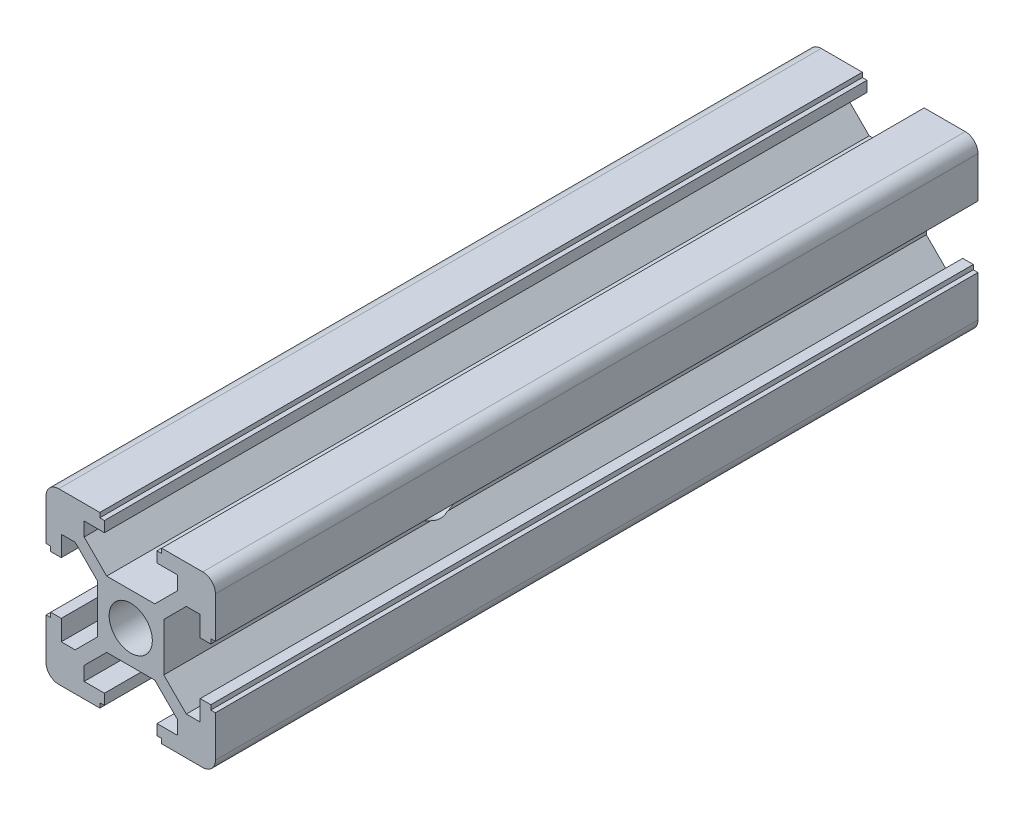
SolidWorks part; units mm, degrees
material "6063-T5"
ref_plane "前视基准面" through (0, 0, 0) normal (0, 0, 1) x (1, 0, 0)
ref_plane "上视基准面" through (0, 0, 0) normal (0, 1, 0) x (1, 0, 0)
ref_plane "右视基准面" through (0, 0, 0) normal (1, 0, 0) x (0, 0, -1)
sketch "草图2" plane through (0, 0, 0) normal (0, 0, 1) x (1, 0, 0)
  line L0 (-3.9, 2.8393) -> (-6.5607, 5.5)
  line L1 (-2.8393, 3.9) -> (2.8393, 3.9)
  line L2 (-3.9, 2.8393) -> (-3.9, -2.8393)
  line L3 (-2.8393, -3.9) -> (2.8393, -3.9)
  line L4 (3.9, 2.8393) -> (3.9, -2.8393)
  line L5 (-3.9, 3.9) -> (3.9, -3.9) construction
  line L6 (-3.9, -3.9) -> (3.9, 3.9) construction
  line L7 (-2.8393, 3.9) -> (-5.5, 6.5607)
  line L8 (-5.5, 6.5607) -> (-5.5, 8.2)
  line L9 (-5.5, 8.2) -> (-3.1, 8.2)
  line L10 (-3.1, 8.2) -> (-3.1, 9.45)
  line L11 (-3.1, 9.45) -> (-3.65, 9.45)
  line L12 (-3.65, 9.45) -> (-3.65, 10)
  line L13 (-3.65, 10) -> (-8.5, 10)
  line L14 (-6.5607, 5.5) -> (-8.2, 5.5)
  line L15 (-10, 3.65) -> (-10, 8.5)
  line L16 (-9.45, 3.65) -> (-10, 3.65)
  line L17 (-9.45, 3.1) -> (-9.45, 3.65)
  line L18 (-8.2, 3.1) -> (-9.45, 3.1)
  line L19 (-8.2, 5.5) -> (-8.2, 3.1)
  line L20 (2.8393, 3.9) -> (5.5, 6.5607)
  line L21 (3.9, 2.8393) -> (6.5607, 5.5)
  line L22 (6.5607, 5.5) -> (8.2, 5.5)
  line L23 (8.2, 5.5) -> (8.2, 3.1)
  line L24 (8.2, 3.1) -> (9.45, 3.1)
  line L25 (9.45, 3.1) -> (9.45, 3.65)
  line L26 (9.45, 3.65) -> (10, 3.65)
  line L27 (10, 3.65) -> (10, 8.5)
  line L28 (5.5, 6.5607) -> (5.5, 8.2)
  line L29 (3.65, 10) -> (8.5, 10)
  line L30 (3.65, 9.45) -> (3.65, 10)
  line L31 (3.1, 9.45) -> (3.65, 9.45)
  line L32 (3.1, 8.2) -> (3.1, 9.45)
  line L33 (5.5, 8.2) -> (3.1, 8.2)
  line L34 (3.9, -2.8393) -> (6.5607, -5.5)
  line L35 (2.8393, -3.9) -> (5.5, -6.5607)
  line L36 (5.5, -6.5607) -> (5.5, -8.2)
  line L37 (5.5, -8.2) -> (3.1, -8.2)
  line L38 (3.1, -8.2) -> (3.1, -9.45)
  line L39 (3.1, -9.45) -> (3.65, -9.45)
  line L40 (3.65, -9.45) -> (3.65, -10)
  line L41 (3.65, -10) -> (8.5, -10)
  line L42 (6.5607, -5.5) -> (8.2, -5.5)
  line L43 (10, -3.65) -> (10, -8.5)
  line L44 (9.45, -3.65) -> (10, -3.65)
  line L45 (9.45, -3.1) -> (9.45, -3.65)
  line L46 (8.2, -3.1) -> (9.45, -3.1)
  line L47 (8.2, -5.5) -> (8.2, -3.1)
  line L48 (-2.8393, -3.9) -> (-5.5, -6.5607)
  line L49 (-3.9, -2.8393) -> (-6.5607, -5.5)
  line L50 (-6.5607, -5.5) -> (-8.2, -5.5)
  line L51 (-8.2, -5.5) -> (-8.2, -3.1)
  line L52 (-8.2, -3.1) -> (-9.45, -3.1)
  line L53 (-9.45, -3.1) -> (-9.45, -3.65)
  line L54 (-9.45, -3.65) -> (-10, -3.65)
  line L55 (-10, -3.65) -> (-10, -8.5)
  line L56 (-5.5, -6.5607) -> (-5.5, -8.2)
  line L57 (-3.65, -10) -> (-8.5, -10)
  line L58 (-3.65, -9.45) -> (-3.65, -10)
  line L59 (-3.1, -9.45) -> (-3.65, -9.45)
  line L60 (-3.1, -8.2) -> (-3.1, -9.45)
  line L61 (-5.5, -8.2) -> (-3.1, -8.2)
  circle A0 centre (0, 0) radius 2.55
  arc A1 (-8.5, 10) -> (-10, 8.5) centre (-8.5, 8.5) ccw
  arc A2 (10, 8.5) -> (8.5, 10) centre (8.5, 8.5) ccw
  arc A3 (8.5, -10) -> (10, -8.5) centre (8.5, -8.5) ccw
  arc A4 (-10, -8.5) -> (-8.5, -10) centre (-8.5, -8.5) ccw
  point P25 (-10, 10)
  point P79 (0, 0)
  dimension "D1" = 5.1
  dimension "D9" = 1.5
  dimension "D2" = 7.8
  dimension "D3" = 1.5
  dimension "D4" = 10
  dimension "D5" = 3.1
  dimension "D6" = 0.55
  dimension "D7" = 1.8
  dimension "D8" = 5.5
  dimension "D11" = 3.9
  dimension "D10" = 4
extrude "凸台-拉伸1" add sketch "草图2" along normal blind 90
sketch "草图3" plane through (10, 0, 0) normal (1, 0, 0) x (0, 0, -1)
  circle A0 centre (-57.5, 0) radius 3
  circle A1 centre (-302.5, 0) radius 3
  dimension "D1" = 6
  dimension "D2" = 6
extrude "切除-拉伸1" cut sketch "草图3" against normal through all
equation "\"90、\"=360"
